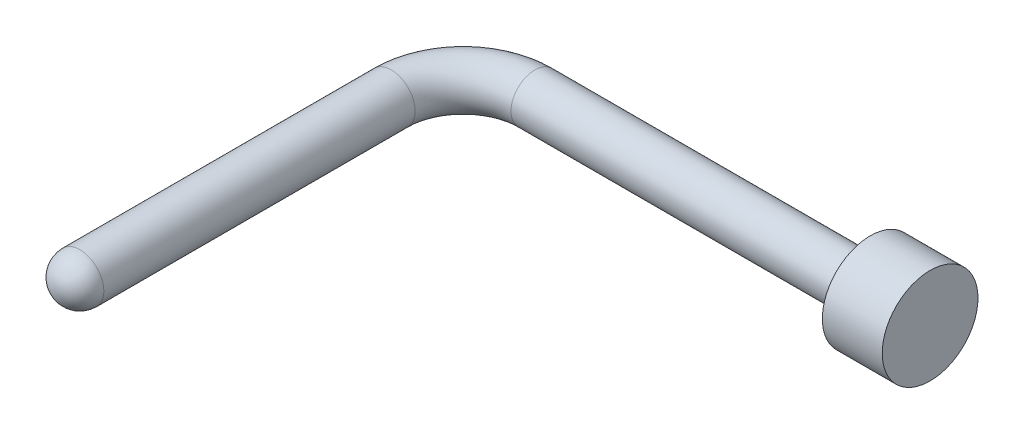
SolidWorks part; units mm, degrees
material "Alumina"
ref_plane "Front Plane" through (0, 0, 0) normal (0, 0, 1) x (1, 0, 0)
ref_plane "Top Plane" through (0, 0, 0) normal (0, 1, 0) x (1, 0, 0)
ref_plane "Right Plane" through (0, 0, 0) normal (1, 0, 0) x (0, 0, -1)
sketch "Sketch1" plane through (0, 0, 0) normal (0, 1, 0) x (1, 0, 0)
  line L0 (0, -17) -> (0, -3)
  line L1 (3, 0) -> (17, 0)
  arc A0 (0, -3) -> (3, 0) centre (3, -3) cw
  point P6 (0, 0)
  dimension "D1" = 3
  dimension "D2" = 17
ref_plane "Plane1" through (17, 0, 0) normal (1, 0, 0) x (0, 0, -1)
sketch "Sketch2" plane through (17, 0, 0) normal (1, 0, 0) x (0, 0, -1)
  circle A0 centre (0, 0) radius 1
  dimension "D1" = 2
sweep "Sweep2" add profiles "Sketch2" path "Sketch1"
fillet "Fillet1" radius 1 1 edges at (-1, 0, 17)
sketch "Sketch3" plane through (17, 0, 0) normal (1, 0, 0) x (0, 0, -1)
  circle A0 centre (0, 0) radius 2
  dimension "D1" = 4
extrude "Boss-Extrude1" add sketch "Sketch3" along normal blind 2.5
